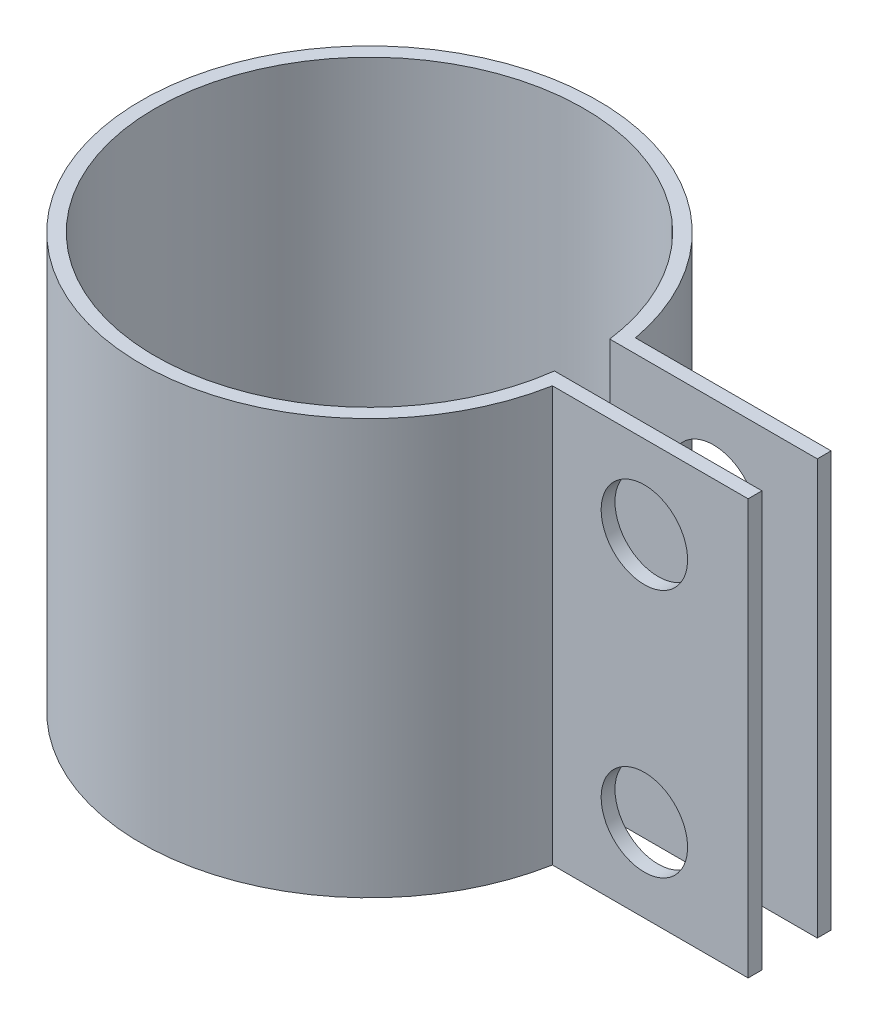
SolidWorks part; units mm, degrees
material "A-玻璃纤维"
ref_plane "前视基准面" through (0, 0, 0) normal (0, 0, 1) x (1, 0, 0)
ref_plane "上视基准面" through (0, 0, 0) normal (0, 1, 0) x (1, 0, 0)
ref_plane "右视基准面" through (0, 0, 0) normal (1, 0, 0) x (0, 0, -1)
sketch "草图2" plane through (0, 0, 0) normal (0, 1, 0) x (1, 0, 0)
  line L0 (0, 0) -> (5.1428, 0) construction
  line L1 (3.0741, 0.4) -> (6.0741, 0.4)
  line L3 (6.0741, -0.4) -> (3.0741, -0.4)
  line L4 (3.245, -0.6) -> (6.0741, -0.6)
  line L5 (6.0741, -0.6) -> (6.0741, -0.4)
  line L6 (3.245, 0.6) -> (6.0741, 0.6)
  line L7 (6.0741, 0.6) -> (6.0741, 0.4)
  arc A0 (3.0741, 0.4) -> (3.0741, -0.4) centre (0, 0) ccw
  arc A1 (3.245, 0.6) -> (3.245, -0.6) centre (0, 0) ccw
  dimension "D1" = 3.1
  dimension "D4" = 0.2
  dimension "D2" = 0.8
  dimension "D3" = 3
  dimension "D5" = 0.2
  dimension "D6" = 0.2
extrude "凸台-拉伸1" add sketch "草图2" along normal blind 6
sketch "草图6" plane through (0, 0, -0.6) normal (0, 0, -1) x (-1, 0, 0)
  line L0 (-4.5741, 4.8) -> (-4.5741, 1.2) construction
  line L1 (-6.0741, 6) -> (-3.245, 6) construction
  line L2 (-6.0741, 6) -> (-6.0741, 0) construction
  line L3 (-6.0741, 0) -> (-3.245, 0) construction
  point P3 (-4.5741, 4.8)
  point P4 (-4.5741, 1.2)
  dimension "D2" = 1.2
  dimension "D3" = 1.5
  dimension "D4" = 1.2
hole_wizard "M1.6 螺纹孔1" positions "草图13" profile "草图14" tap size "M1.6" standard "GB" end condition through all
sketch "草图13" plane through (0, 0, -0.6) normal (0, 0, -1) x (-1, 0, 0)
  point P0 (-4.5741, 4.8)
  point P3 (-4.5741, 1.2)
sketch "草图14" plane through (4.5741, 4.8, -0.6) normal (1, 0, 0) x (0, 1, 0)
  line L0 (0, 0) -> (0, 3.9)
  line L1 (0, 3.9) -> (0.625, 3.9)
  line L2 (0.625, 3.9) -> (0.625, 0.2)
  line L3 (0.625, 0.2) -> (0.825, 0)
  line L5 (0.825, 0) -> (0, 0)
  line L6 (-0.625, 0.2) -> (-0.825, 0) construction
  line L11 (0, -6.35) -> (0, 107.95) construction
  dimension "通孔螺纹孔钻头直径" = 1.25
  dimension "通孔螺纹孔钻头深度" = 3.9
  dimension "近端锥形沉头孔直径" = 1.65
  dimension "近端锥形沉头孔角度" = 90
cosmetic thread "孔螺纹线1"
cosmetic thread "孔螺纹线2"
